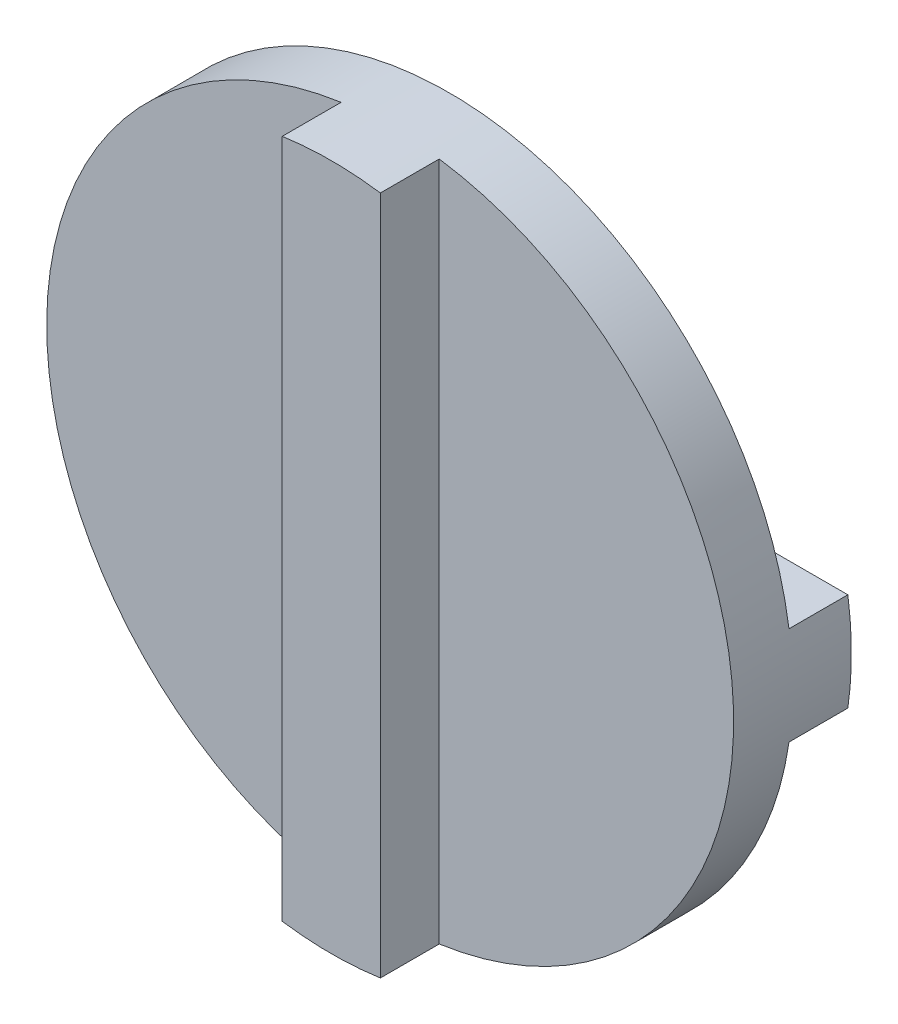
SolidWorks part; units mm, degrees
material "Gray Cast Iron"
ref_plane "Front Plane" through (0, 0, 0) normal (0, 0, 1) x (1, 0, 0)
ref_plane "Top Plane" through (0, 0, 0) normal (0, 1, 0) x (1, 0, 0)
ref_plane "Right Plane" through (0, 0, 0) normal (1, 0, 0) x (0, 0, -1)
sketch "Sketch1" plane through (0, 0, 0) normal (0, 0, 1) x (1, 0, 0)
  circle A0 centre (0, 0) radius 175
  dimension "D1" = 350
extrude "Boss-Extrude1" add sketch "Sketch1" along normal blind 30 contours A0
sketch "Sketch2" plane through (0, 0, 30) normal (0, 0, 1) x (1, 0, 0)
  line L0 (0, 186.926) -> (0, -186.926) construction
  line L1 (25, 173.2051) -> (25, -173.2051)
  line L2 (-25, 173.2051) -> (-25, -173.2051)
  arc A0 (25, 173.2051) -> (-25, 173.2051) centre (0, 0) ccw
  arc A1 (-25, -173.2051) -> (25, -173.2051) centre (0, 0) ccw
  point P5 (0, 0)
  dimension "D4" = 350
  dimension "D1" = 25
  dimension "D2" = 25
  dimension "D3" = 50
extrude "Boss-Extrude2" add sketch "Sketch2" along normal blind 30 contours L2 A1 L1 A0
sketch "Sketch3" plane through (0, 0, 0) normal (0, 0, -1) x (-1, 0, 0)
  line L0 (-216.1257, 0) -> (216.1257, 0) construction
  line L1 (-173.2051, 25) -> (173.2051, 25)
  line L2 (-173.2051, -25) -> (173.2051, -25)
  arc A0 (-173.2051, 25) -> (-173.2051, -25) centre (0, 0) ccw
  arc A1 (173.2051, -25) -> (173.2051, 25) centre (0, 0) ccw
  point P4 (0, 0)
  dimension "D4" = 350
  dimension "D1" = 25
  dimension "D2" = 25
  dimension "D3" = 50
extrude "Boss-Extrude3" add sketch "Sketch3" along normal blind 30 contours L1 A1 L2 A0
